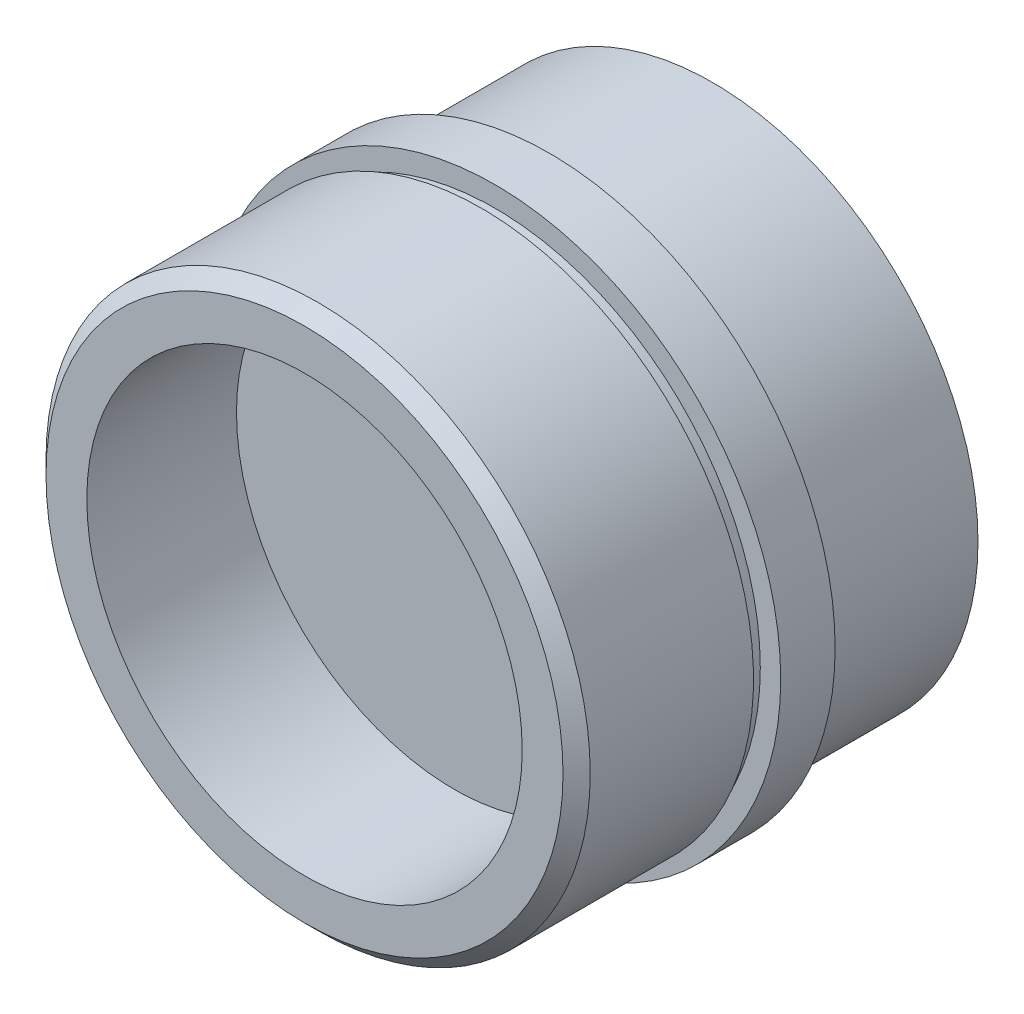
SolidWorks part; units mm, degrees
ref_plane "前视基准面" through (0, 0, 0) normal (0, 0, 1) x (1, 0, 0)
ref_plane "上视基准面" through (0, 0, 0) normal (0, 1, 0) x (1, 0, 0)
ref_plane "右视基准面" through (0, 0, 0) normal (1, 0, 0) x (0, 0, -1)
sketch "草图1" plane through (0, 0, 0) normal (0, 0, 1) x (1, 0, 0)
  circle A0 centre (0, 0) radius 19.5
  circle A1 centre (0, 0) radius 16
  dimension "D1" = 32
extrude "拉伸1" add sketch "草图1" along normal blind 12
sketch "草图2" plane through (0, 0, 12) normal (0, 0, 1) x (1, 0, 0)
  circle A0 centre (0, 0) radius 16
  circle A1 centre (0, 0) radius 21
  dimension "D1" = 32
extrude "拉伸2" add sketch "草图2" along normal blind 4
sketch "草图3" plane through (0, 0, 16) normal (0, 0, 1) x (1, 0, 0)
  circle A1 centre (0, 0) radius 20
extrude "拉伸3" add sketch "草图3" along normal blind 3
sketch "草图4" plane through (0, 0, 19) normal (0, 0, 1) x (1, 0, 0)
  circle A0 centre (0, 0) radius 20
  circle A1 centre (0, 0) radius 16
  dimension "D1" = 32
extrude "拉伸4" add sketch "草图4" along normal blind 14
ref_plane "基准面1" through (0, 0, 30) normal (0, 0, 1) x (1, 0, 0)
sketch "草图6" plane through (0, 0, 30) normal (0, 0, 1) x (1, 0, 0)
  circle A0 centre (0, 0) radius 19
  circle A1 centre (0, 0) radius 20
extrude "切除-拉伸1" cut sketch "草图6" along normal blind 1.5
sketch "草图7" plane through (0, 0, 33) normal (0, 0, 1) x (1, 0, 0)
  circle A0 centre (0, 0) radius 20
extrude "切除-拉伸2" cut sketch "草图7" against normal up to surface (3 mm away) up to face at (20, 0, 30)
chamfer "倒角1" distance 1 angle 45 1 edges at (20, 0, 30)
sketch "草图8" plane through (0, 0, 0) normal (0, 1, 0) x (1, 0, 0)
  line L0 (0, 0) -> (0, -33.149) construction
  line L1 (-20, -16) -> (-19.5, -16)
  line L2 (-20, -16) -> (-20, -17)
  line L3 (-20, -17) -> (-19.5, -17)
  line L4 (-19.5, -16) -> (-19.5, -17)
  dimension "D1" = 1
  dimension "D2" = 0.5
revolve "切除-旋转1" cut sketch "草图8" angle 360 about L0
